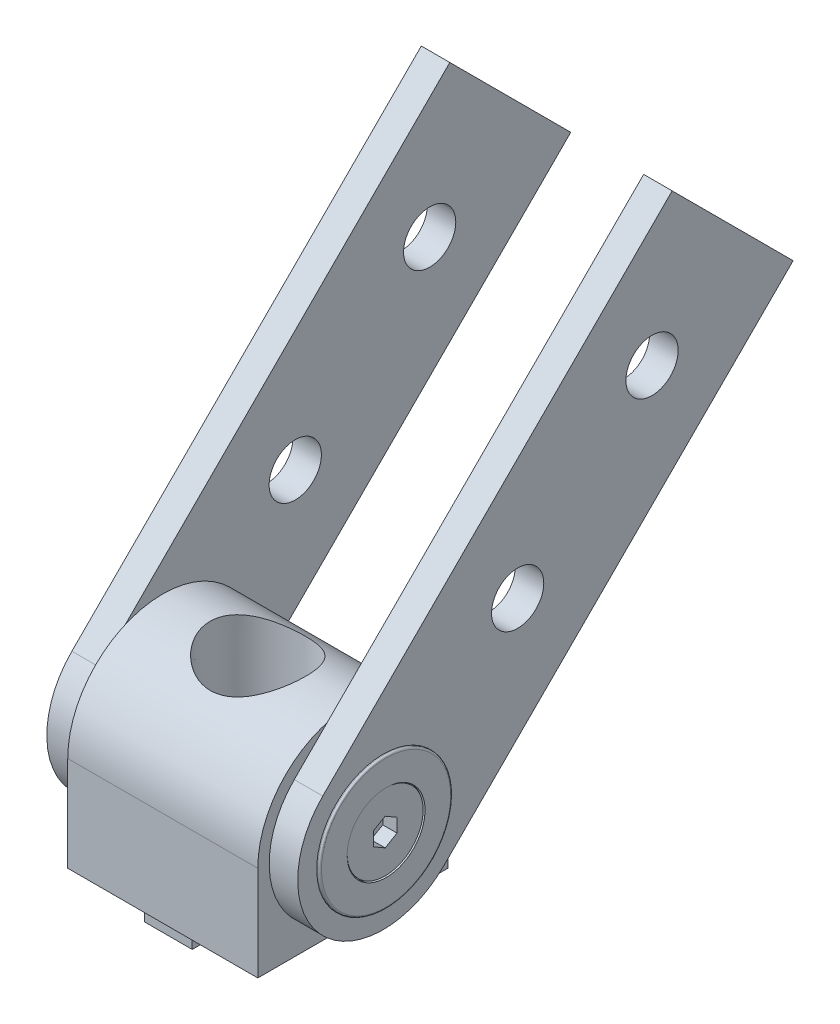
SolidWorks part; units mm, degrees
ref_plane "Front Plane" through (0, 0, 0) normal (0, 0, 1) x (1, 0, 0)
ref_plane "Top Plane" through (0, 0, 0) normal (0, 1, 0) x (1, 0, 0)
ref_plane "Right Plane" through (0, 0, 0) normal (1, 0, 0) x (0, 0, -1)
sketch "Sketch0" plane through (0, 0, 0) normal (1, 0, 0) x (0, 0, -1)
  line L0 (0, 0) -> (0, 20) construction
  line L1 (-10, 0) -> (10, 0) construction
  line L2 (-10, 10) -> (-10, 0) construction
  line L3 (10, 10) -> (10, 0) construction
  arc A0 (10, 10) -> (-10, 10) centre (0, 10) ccw construction
  point P3 (0, 5)
  dimension "D1" = 20
  dimension "D2" = 5
  dimension "D3" = 20
  dimension "D4" = 10
sketch "Sketch1" plane through (0, 0, 0) normal (1, 0, 0) x (0, 0, -1)
  line L0 (-10, 10) -> (-10, 0) construction
  line L1 (-10, 0) -> (10, 0) construction
  line L2 (10, 10) -> (10, 0) construction
  line L3 (-10, 10) -> (-10, 0)
  line L4 (-10, 0) -> (10, 0)
  line L5 (10, 10) -> (10, 0)
  arc A0 (10, 10) -> (-10, 10) centre (0, 10) ccw construction
  arc A1 (10, 10) -> (-10, 10) centre (0, 10) ccw
  circle A2 centre (0, 10) radius 1.65
  dimension "D1" = 3.3
extrude "Boss-Extrude1" add sketch "Sketch1" along normal mid plane 20 separate body
ref_plane "Plane1" through (0, 5, 0) normal (0, 1, 0) x (-1, 0, 0)
sketch "Sketch2" plane through (0, 5, 0) normal (0, 1, 0) x (-1, 0, 0)
  line L0 (10.2, 0) -> (-10.2, 0) construction
  circle A0 centre (0, 0) radius 4.5
  dimension "D1" = 9
  dimension "D2" = 20.4
extrude "Cut-Extrude1" cut sketch "Sketch2" along normal through all draft 2 draft outward yes
sketch "Sketch3" plane through (0, 5, 0) normal (0, 1, 0) x (1, 0, 0)
  circle A0 centre (0, 0) radius 2.65
  dimension "D1" = 5.3
extrude "Cut-Extrude2" cut sketch "Sketch3" against normal through all
sketch "Sketch4" plane through (0, 0, 0) normal (0, -1, 0) x (1, 0, 0)
  line L0 (0, 4.9) -> (0, -4.9) construction
  line L1 (-2.5, 9.4) -> (2.5, 9.4)
  line L2 (-2.5, 9.4) -> (-2.5, 4.9)
  line L3 (-2.5, 4.9) -> (2.5, 4.9)
  line L4 (2.5, 9.4) -> (2.5, 4.9)
  line L5 (-4.9, 0) -> (4.9, 0) construction
  line L6 (2.5, -9.4) -> (2.5, -4.9)
  line L7 (-4.9, 2.5) -> (-9.4, 2.5)
  line L8 (-4.9, 2.5) -> (-4.9, -2.5)
  line L9 (-4.9, -2.5) -> (-9.4, -2.5)
  line L10 (-9.4, 2.5) -> (-9.4, -2.5)
  line L11 (-2.5, -4.9) -> (2.5, -4.9)
  line L12 (-2.5, -9.4) -> (-2.5, -4.9)
  line L13 (-2.5, -9.4) -> (2.5, -9.4)
  line L14 (9.4, 2.5) -> (9.4, -2.5)
  line L15 (4.9, -2.5) -> (9.4, -2.5)
  line L16 (4.9, 2.5) -> (4.9, -2.5)
  line L17 (4.9, 2.5) -> (9.4, 2.5)
  line L18 (10, 10) -> (-10, 10) construction
  dimension "D1" = 0.6
  dimension "D2" = 4.5
  dimension "D3" = 5
extrude "Cut-Extrude3" cut sketch "Sketch4" against normal blind 4.1
sketch "Sketch5" plane through (0, 0, 0) normal (0, -1, 0) x (1, 0, 0)
  line L12 (2.5, 9.4) -> (-2.5, 9.4)
  line L13 (2.5, 4.9) -> (2.5, 9.4)
  line L14 (-2.5, 4.9) -> (2.5, 4.9)
  line L15 (-2.5, 9.4) -> (-2.5, 4.9)
  line L16 (2.5, 9.4) -> (-2.5, 9.4)
  line L17 (2.5, 4.9) -> (2.5, 9.4)
  line L18 (-2.5, 4.9) -> (2.5, 4.9)
  line L19 (-2.5, 9.4) -> (-2.5, 4.9)
  line L28 (-2.5, -4.9) -> (-2.5, -9.4)
  line L29 (2.5, -4.9) -> (-2.5, -4.9)
  line L30 (2.5, -9.4) -> (2.5, -4.9)
  line L31 (-2.5, -9.4) -> (2.5, -9.4)
  line L32 (-2.5, -4.9) -> (-2.5, -9.4)
  line L33 (2.5, -4.9) -> (-2.5, -4.9)
  line L34 (2.5, -9.4) -> (2.5, -4.9)
  line L35 (-2.5, -9.4) -> (2.5, -9.4)
  dimension "D2" = 0
  dimension "D4" = 0
extrude "Boss-Extrude2" add sketch "Sketch5" along normal blind 1.45 and the other way up to surface (4.1 mm away) separate body other way up to face at (0, 4.1, 7.15)
sketch "Sketch6" plane through (0, 0, 0) normal (1, 0, 0) x (0, 0, -1)
  line L0 (-6.364, 3.636) -> (36.7696, 46.7696) construction
  line L1 (30.4056, 53.1335) -> (43.1335, 40.4056)
  line L2 (30.4056, 53.1335) -> (-6.364, 16.364)
  line L3 (43.1335, 40.4056) -> (6.364, 3.636)
  line L4 (0, 0) -> (0, 20) construction
  arc A0 (-6.364, 16.364) -> (6.364, 3.636) centre (0, 10) ccw
  circle A1 centre (28.2843, 38.2843) radius 2.75
  circle A2 centre (14.1421, 24.1421) radius 2.75
  circle A4 centre (0, 10) radius 7
  dimension "D4" = 5.5
  dimension "D7" = 14
  dimension "D1" = 18
  dimension "D2" = 45
  dimension "D3" = 61
  dimension "D5" = 20
  dimension "D6" = 20
extrude "Boss-Extrude3" add sketch "Sketch6" against normal blind 3 from vertex at -10.2 separate body starting at point (-10.2, 5, 0)
sketch "Sketch7" plane through (0, 0, 0) normal (0, 0, 1) x (1, 0, 0)
  line L0 (-5.4, 10) -> (-5.4, 11.5)
  line L1 (-5.4, 11.5) -> (-5.9, 12)
  line L2 (-13.4, 14) -> (-13.4, 10)
  line L3 (-13.4, 10) -> (-5.4, 10)
  line L4 (-5.4, 10) -> (0, 10) construction
  line L6 (-5.9, 12) -> (-11.1, 12)
  line L7 (-11.1, 12) -> (-13.1, 14)
  line L8 (-13.1, 14) -> (-13.4, 14)
  line L9 (-13.2, 16.364) -> (-13.2, 1) construction
  dimension "D1" = 8
  dimension "D2" = 8
  dimension "D3" = 0.2
  dimension "D4" = 0.3
  dimension "D6" = 45
  dimension "D7" = 4
  dimension "D8" = 3
  dimension "D9" = 45
revolve "Revolve1" add sketch "Sketch7" angle 360 mid plane about L4
sketch "Sketch8" plane through (0, 0, 0) normal (0, 0, 1) x (1, 0, 0)
  line L0 (0, 10) -> (-13.2, 10) construction
  line L1 (-13.3, 17) -> (-11.9, 17)
  line L2 (-13.5, 16.8) -> (-13.5, 14.1)
  line L3 (-13.5, 14.1) -> (-13.2, 14.1)
  line L4 (-11.7, 16.8) -> (-11.7, 13.1)
  line L5 (-13.2, 16.364) -> (-13.2, 1) construction
  line L6 (-13.2, 14.1) -> (-12.2, 13.1)
  line L8 (-12.2, 13.1) -> (-11.7, 13.1)
  line L9 (-13.4, 14) -> (-13.4, 10) construction
  line L10 (-11.1, 12) -> (-13.1, 14) construction
  arc A0 (-13.3, 17) -> (-13.5, 16.8) centre (-13.3, 16.8) ccw
  arc A1 (-11.9, 17) -> (-11.7, 16.8) centre (-11.9, 16.8) cw
  dimension "D3" = 0.2
  dimension "D4" = 0.1
  dimension "D1" = 0.3
  dimension "D2" = 1.8
  dimension "D5" = 14
  dimension "D6" = 6.2
  dimension "D7" = 8.2
revolve "Revolve2" add sketch "Sketch8" angle 360 about L0
sketch "Sketch9" plane through (-13.4, 0, 0) normal (-1, 0, 0) x (0, 0, 1)
  line L1 (0, 11.4434) -> (-1.25, 10.7217)
  line L2 (-1.25, 10.7217) -> (-1.25, 9.2783)
  line L3 (-1.25, 9.2783) -> (0, 8.5566)
  line L4 (0, 8.5566) -> (1.25, 9.2783)
  line L5 (1.25, 9.2783) -> (1.25, 10.7217)
  line L6 (1.25, 10.7217) -> (0, 11.4434)
  circle A0 centre (0, 10) radius 1.25 construction
  dimension "D1" = 2.5
extrude "Cut-Extrude4" cut sketch "Sketch9" against normal blind 1.5
mirror "Mirror1" about plane through (0, 0, 0) normal (1, 0, 0) of bodies 137 142 150 139 143
